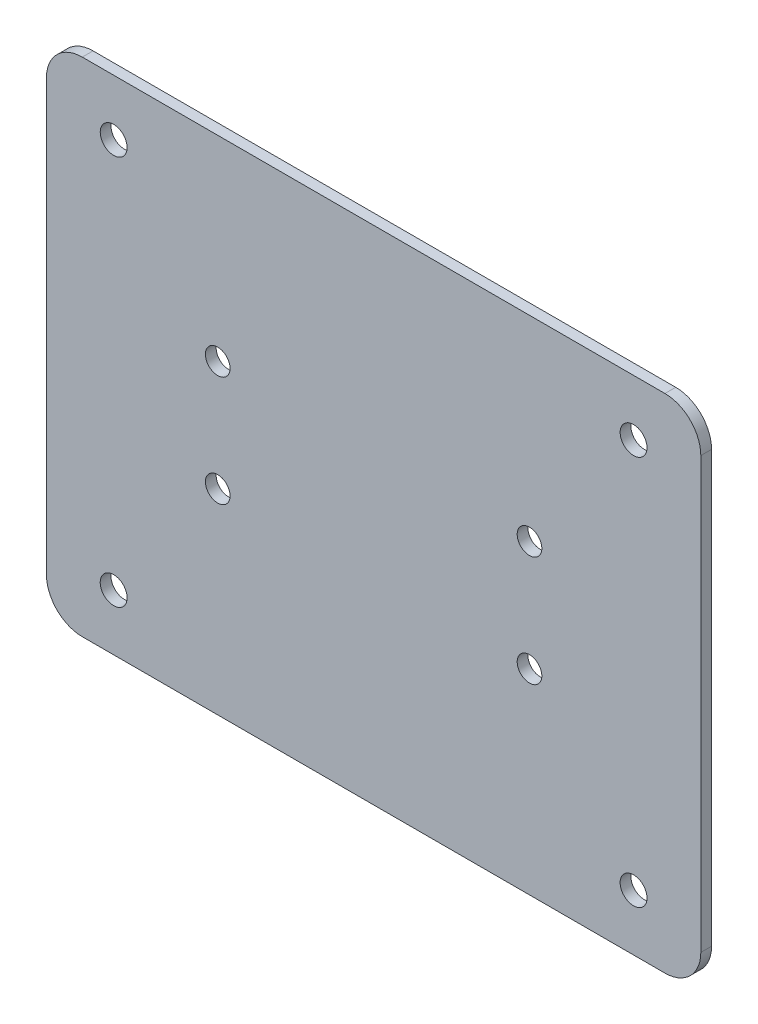
SolidWorks part; units mm, degrees
ref_plane "Front Plane" through (0, 0, 0) normal (0, 0, 1) x (1, 0, 0)
ref_plane "Top Plane" through (0, 0, 0) normal (0, 1, 0) x (1, 0, 0)
ref_plane "Right Plane" through (0, 0, 0) normal (1, 0, 0) x (0, 0, -1)
sketch "Sketch1" plane through (0, 0, 0) normal (0, 0, 1) x (1, 0, 0)
  line L0 (36.5, 56) -> (36.5, 0) construction
  line L1 (0, 0) -> (73, 0)
  line L2 (0, 0) -> (0, 56)
  line L3 (0, 56) -> (73, 56)
  line L4 (73, 0) -> (73, 56)
  line L5 (0, 28) -> (73, 28) construction
  circle A0 centre (7.5, 6.25) radius 1.5
  circle A1 centre (65.5, 6.25) radius 1.5
  circle A2 centre (65.5, 49.75) radius 1.5
  circle A3 centre (7.5, 49.75) radius 1.5
  dimension "D5" = 3
  dimension "D1" = 73
  dimension "D2" = 56
  dimension "D3" = 29
  dimension "D4" = 21.75
extrude "Boss-Extrude1" add sketch "Sketch1" along normal blind 1.2
fillet "Fillet1" radius 4 4 edges at (0, 0, 0.6) (0, 56, 0.6) (73, 56, 0.6) (73, 0, 0.6)
sketch "Sketch2" plane through (0, 0, 1.2) normal (0, 0, 1) x (1, 0, 0)
  line L0 (36.5, 0) -> (36.5, 56) construction
  line L1 (4, 0) -> (69, 0) construction
  line L2 (69, 56) -> (4, 56) construction
  line L3 (73, 28) -> (0, 28) construction
  line L4 (73, 4) -> (73, 52) construction
  line L5 (0, 52) -> (0, 4) construction
  circle A0 centre (53.89, 21.84) radius 1.375
  circle A1 centre (53.89, 34.16) radius 1.375
  circle A2 centre (19.11, 21.84) radius 1.375
  circle A3 centre (19.11, 34.16) radius 1.375
  dimension "D3" = 2.75
  dimension "D1" = 17.39
  dimension "D2" = 6.16
extrude "Cut-Extrude1" cut sketch "Sketch2" against normal up to next
